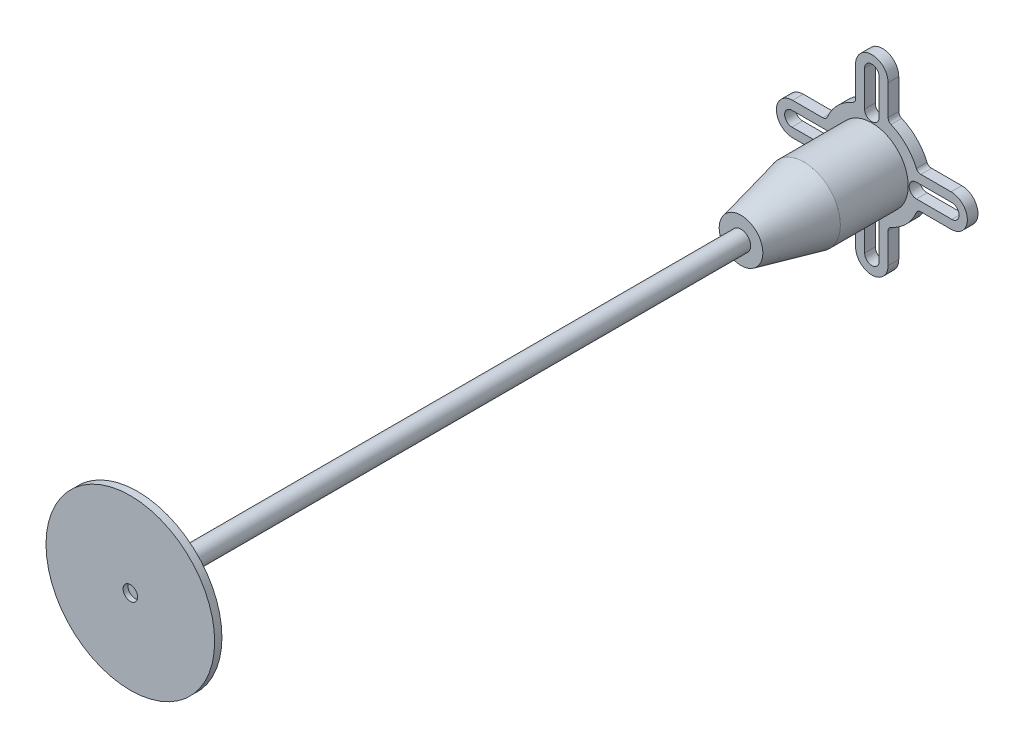
SolidWorks part; units mm, degrees
ref_plane "Front Plane" through (0, 0, 0) normal (0, 0, 1) x (1, 0, 0)
ref_plane "Top Plane" through (0, 0, 0) normal (0, 1, 0) x (1, 0, 0)
ref_plane "Right Plane" through (0, 0, 0) normal (1, 0, 0) x (0, 0, -1)
sketch "Sketch1" plane through (0, 0, 0) normal (0, 0, 1) x (1, 0, 0)
  line L0 (0, 0) -> (0, 16.35) construction
  line L1 (0, 16.35) -> (-3.35, 16.35) construction
  line L2 (-3.35, 16.35) -> (-3.35, 10.1033)
  line L3 (3.35, 16.35) -> (3.35, 10.1033)
  line L4 (16.35, 3.35) -> (10.1033, 3.35)
  line L5 (16.35, -3.35) -> (10.1033, -3.35)
  line L6 (3.35, -16.35) -> (3.35, -10.1033)
  line L7 (-3.35, -16.35) -> (-3.35, -10.1033)
  line L8 (-16.35, -3.35) -> (-10.1033, -3.35)
  line L9 (-16.35, 3.35) -> (-10.1033, 3.35)
  line L10 (0, 0) -> (16.5, 0) construction
  line L11 (16.5, 0) -> (16.5, 1.5) construction
  line L12 (16.5, 1.5) -> (9.2, 1.5)
  line L13 (9.2, 1.5) -> (9.2, 0) construction
  line L14 (9.2, -1.5) -> (16.5, -1.5)
  line L15 (-1.5, -9.2) -> (-1.5, -16.5)
  line L16 (1.5, -16.5) -> (1.5, -9.2)
  line L17 (-9.2, 1.5) -> (-16.5, 1.5)
  line L18 (-16.5, -1.5) -> (-9.2, -1.5)
  line L19 (1.5, 9.2) -> (1.5, 16.5)
  line L20 (-1.5, 16.5) -> (-1.5, 9.2)
  arc A0 (-3.9545, 9.1849) -> (-9.1849, 3.9545) centre (0, 0) ccw
  arc A1 (3.35, 16.35) -> (-3.35, 16.35) centre (0, 16.35) ccw
  arc A2 (16.35, -3.35) -> (16.35, 3.35) centre (16.35, 0) ccw
  arc A3 (-3.35, -16.35) -> (3.35, -16.35) centre (0, -16.35) ccw
  arc A4 (-16.35, 3.35) -> (-16.35, -3.35) centre (-16.35, 0) ccw
  arc A5 (-9.1849, -3.9545) -> (-3.9545, -9.1849) centre (0, 0) ccw
  arc A6 (3.9545, -9.1849) -> (9.1849, -3.9545) centre (0, 0) ccw
  arc A7 (9.1849, 3.9545) -> (3.9545, 9.1849) centre (0, 0) ccw
  arc A8 (-3.9545, 9.1849) -> (-3.35, 10.1033) centre (-4.35, 10.1033) ccw
  arc A9 (3.9545, 9.1849) -> (3.35, 10.1033) centre (4.35, 10.1033) cw
  arc A10 (10.1033, 3.35) -> (9.1849, 3.9545) centre (10.1033, 4.35) cw
  arc A11 (10.1033, -3.35) -> (9.1849, -3.9545) centre (10.1033, -4.35) ccw
  arc A12 (3.9545, -9.1849) -> (3.35, -10.1033) centre (4.35, -10.1033) ccw
  arc A13 (-3.35, -10.1033) -> (-3.9545, -9.1849) centre (-4.35, -10.1033) ccw
  arc A14 (-9.1849, -3.9545) -> (-10.1033, -3.35) centre (-10.1033, -4.35) ccw
  arc A15 (-10.1033, 3.35) -> (-9.1849, 3.9545) centre (-10.1033, 4.35) ccw
  arc A16 (16.5, -1.5) -> (16.5, 1.5) centre (16.5, 0) ccw
  arc A17 (9.2, 1.5) -> (9.2, -1.5) centre (9.2, 0) ccw
  arc A18 (1.5, -9.2) -> (-1.5, -9.2) centre (0, -9.2) ccw
  arc A19 (-1.5, -16.5) -> (1.5, -16.5) centre (0, -16.5) ccw
  arc A20 (-9.2, -1.5) -> (-9.2, 1.5) centre (-9.2, 0) ccw
  arc A21 (-16.5, 1.5) -> (-16.5, -1.5) centre (-16.5, 0) ccw
  arc A22 (-1.5, 9.2) -> (1.5, 9.2) centre (0, 9.2) ccw
  arc A23 (1.5, 16.5) -> (-1.5, 16.5) centre (0, 16.5) ccw
  point P25 (0, 0)
  point P66 (0, 0)
  dimension "D1" = 20
  dimension "D5" = 1
  dimension "D6" = 1
  dimension "D2" = 16.35
  dimension "D3" = 3.35
  dimension "D7" = 16.5
  dimension "D8" = 1.5
  dimension "D9" = 7.3
  dimension "D4" = 4
  dimension "D10" = 4
extrude "Boss-Extrude1" add sketch "Sketch1" along normal blind 2.2
ref_plane "Plane1" through (0, 0, 2.2) normal (0, 0, 1) x (1, 0, 0)
sketch "Sketch2" plane through (0, 0, 2.2) normal (0, 0, 1) x (1, 0, 0)
  circle A0 centre (0, 0) radius 7.5
  dimension "D1" = 15
extrude "Boss-Extrude2" add sketch "Sketch2" along normal blind 14
sketch "Sketch3" plane through (0, 0, 0) normal (0, 1, 0) x (1, 0, 0)
  line L0 (0, -16.2) -> (7.5, -16.2)
  line L1 (-7.5, -16.2) -> (7.5, -16.2) construction
  line L2 (0, -16.2) -> (0, -29.2) construction
  line L3 (0, -29.2) -> (4.5, -29.2)
  line L4 (7.5, -16.2) -> (4.5, -29.2)
  line L5 (0, -16.2) -> (0, -29.2)
  dimension "D1" = 13
  dimension "D2" = 4.5
revolve "Revolve1" add sketch "Sketch3" angle 360 about L5
sketch "Sketch4" plane through (0, 0, 29.2) normal (0, 0, 1) x (1, 0, 0)
  circle A0 centre (0, 0) radius 2
  dimension "D1" = 4
extrude "Boss-Extrude3" add sketch "Sketch4" along normal blind 117
sketch "Sketch5" plane through (0, 0, 0) normal (0, 1, 0) x (1, 0, 0)
  line L0 (0, -146.2) -> (3.4, -146.2)
  line L1 (-2, -146.2) -> (2, -146.2) construction
  line L2 (0, -146.2) -> (0, -153.7)
  line L3 (0, -153.7) -> (7, -153.7)
  line L4 (3.4, -146.2) -> (7, -153.7)
  dimension "D1" = 3.4
  dimension "D2" = 7.5
  dimension "D3" = 7
revolve "Revolve2" add sketch "Sketch5" angle 360 about L2
sketch "Sketch6" plane through (0, 0, 153.7) normal (0, 0, 1) x (1, 0, 0)
  circle A0 centre (0, 0) radius 17.4
  dimension "D1" = 34.8
extrude "Boss-Extrude4" add sketch "Sketch6" along normal blind 1.5
sketch "Sketch7" plane through (0, 0, 155.2) normal (0, 0, 1) x (1, 0, 0)
  circle A0 centre (0, 0) radius 1.5
  dimension "D1" = 3
extrude "Cut-Extrude1" cut sketch "Sketch7" against normal blind 1
